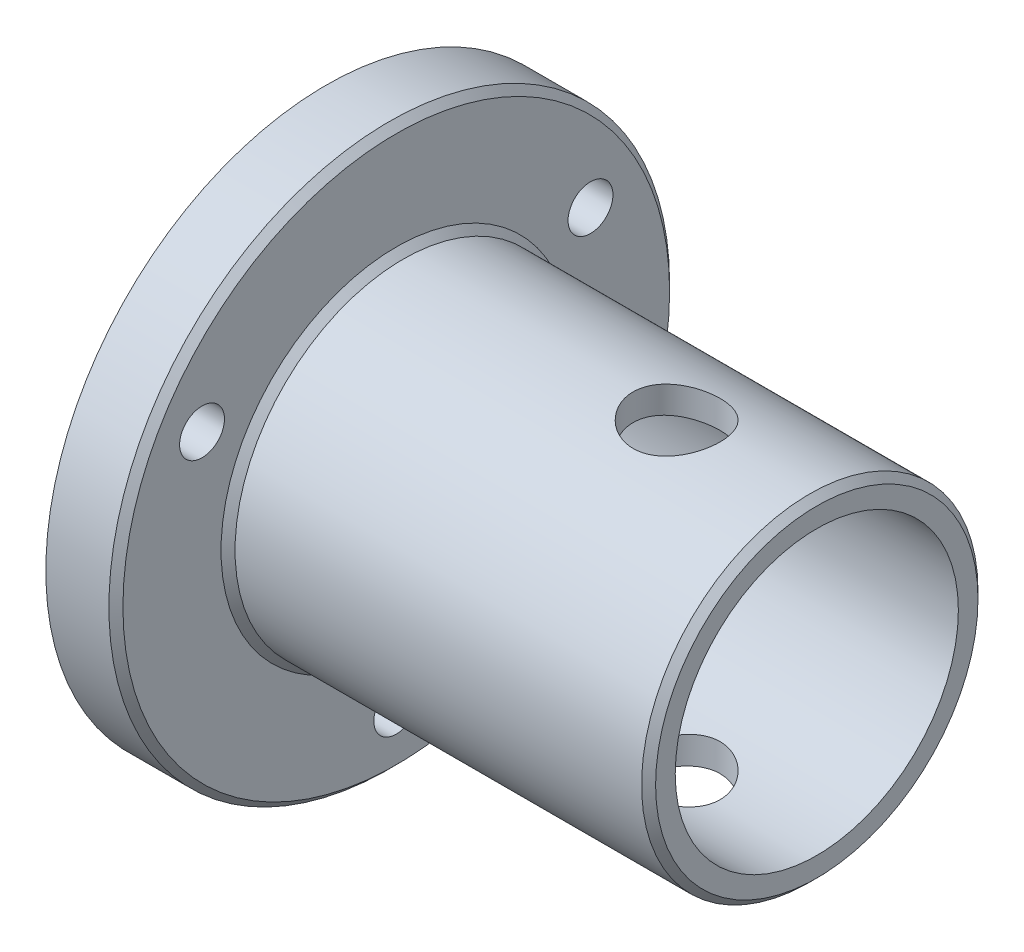
SolidWorks part; units mm, degrees
ref_plane "Front" through (0, 0, 0) normal (0, 0, 1) x (1, 0, 0)
ref_plane "Top" through (0, 0, 0) normal (0, 1, 0) x (1, 0, 0)
ref_plane "Right" through (0, 0, 0) normal (1, 0, 0) x (0, 0, -1)
sketch "草图1" plane through (0, 0, 0) normal (1, 0, 0) x (0, 0, -1)
  line L0 (0, 0) -> (0, -16) construction
  line L1 (0, 0) -> (13.8564, 8) construction
  line L2 (0, 0) -> (-13.8564, 8) construction
  circle A0 centre (0, 0) radius 10
  circle A1 centre (0, 0) radius 20
  circle A2 centre (0, 0) radius 16 construction
  circle A3 centre (0, 0) radius 12
  circle A4 centre (-13.8564, 8) radius 1.6
  circle A5 centre (13.8564, 8) radius 1.6
  circle A6 centre (0, -16) radius 1.6
extrude "凸台-拉伸1" add sketch "草图1" along normal blind 5 contours A1
sketch "草图6" plane through (5, 0, 0) normal (1, 0, 0) x (0, 0, -1)
  circle A0 centre (0, 0) radius 10
  circle A1 centre (0, 0) radius 12
extrude "凸台-拉伸2" add sketch "草图6" along normal blind 30 contours A1
sketch "草图7" plane through (35, 0, 0) normal (1, 0, 0) x (0, 0, -1)
  circle A0 centre (0, 0) radius 10.1
extrude "切除-拉伸2" cut sketch "草图7" against normal blind 30
chamfer "倒角1" distance 0.5 angle 45 1 edges at (35, 0, -12)
sketch "草图8" plane through (0, 0, 0) normal (0, 1, 0) x (1, 0, 0)
  line L0 (5, 0) -> (25, 0) construction
  line L1 (5, -20) -> (5, 20) construction
  circle A0 centre (25, 0) radius 3.1
extrude "切除-拉伸3" cut sketch "草图8" along normal through all both and the other way through all
chamfer "倒角2" distance 0.5 angle 45 1 edges at (5, 0, -20)
chamfer "倒角3" distance 0.5 angle 45 1 edges at (5, 0, -12)
sketch "草图9" plane through (0, 0, 0) normal (-1, 0, 0) x (0, 0, 1)
  circle A0 centre (-13.8564, 8) radius 1.6
  circle A1 centre (13.8564, 8) radius 1.6
  circle A2 centre (0, -16) radius 1.6
extrude "切除-拉伸4" cut sketch "草图9" against normal blind 10
